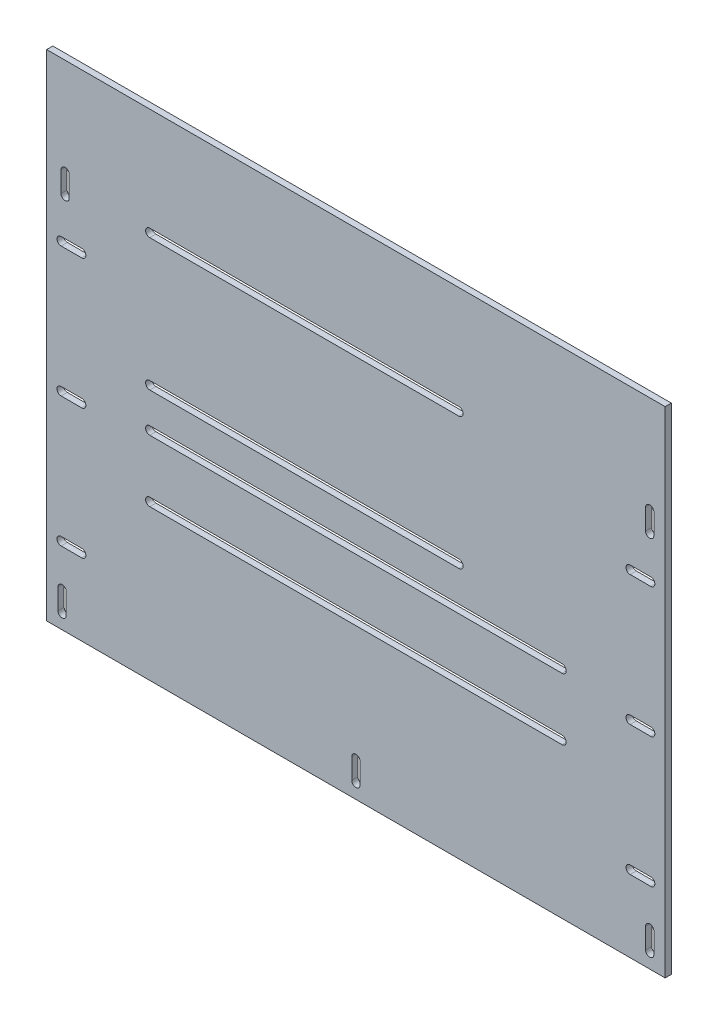
SolidWorks part; units mm, degrees
ref_plane "Front Plane" through (0, 0, 0) normal (0, 0, 1) x (1, 0, 0)
ref_plane "Top Plane" through (0, 0, 0) normal (0, 1, 0) x (1, 0, 0)
ref_plane "Right Plane" through (0, 0, 0) normal (1, 0, 0) x (0, 0, -1)
sketch "Sketch1" plane through (0, 0, 0) normal (0, 0, 1) x (1, 0, 0)
  line L1 (-150, 100) -> (150, 100)
  line L2 (-150, 100) -> (-150, -100)
  line L3 (-150, -100) -> (150, -100)
  line L4 (150, 100) -> (150, -100)
  line L5 (-150, 100) -> (150, -100) construction
  line L6 (-150, -100) -> (150, 100) construction
  point P0 (0, 0)
  dimension "D1" = 200
  dimension "D2" = 300
extrude "Boss-Extrude1" add sketch "Sketch1" along normal blind 3
sketch "Sketch2" plane through (0, 0, 0) normal (0, 0, -1) x (-1, 0, 0)
  line L0 (-100, -25) -> (100, -25) construction
  line L1 (-100, -23) -> (100, -23)
  line L2 (-100, -27) -> (100, -27)
  line L3 (150, 100) -> (150, -100) construction
  line L4 (150, -100) -> (-150, -100) construction
  line L5 (-100, 5) -> (100, 5) construction
  line L6 (-100, 7) -> (100, 7)
  line L7 (-100, 3) -> (100, 3)
  line L8 (-50, 24) -> (100, 24) construction
  line L9 (-50, 26) -> (100, 26)
  line L10 (-50, 22) -> (100, 22)
  line L11 (-50, 88) -> (100, 88) construction
  line L12 (-50, 90) -> (100, 90)
  line L13 (-50, 86) -> (100, 86)
  arc A0 (-100, -23) -> (-100, -27) centre (-100, -25) ccw
  arc A1 (100, -27) -> (100, -23) centre (100, -25) ccw
  arc A2 (-100, 7) -> (-100, 3) centre (-100, 5) ccw
  arc A3 (100, 3) -> (100, 7) centre (100, 5) ccw
  arc A4 (-50, 26) -> (-50, 22) centre (-50, 24) ccw
  arc A5 (100, 22) -> (100, 26) centre (100, 24) ccw
  arc A6 (-50, 90) -> (-50, 86) centre (-50, 88) ccw
  arc A7 (100, 86) -> (100, 90) centre (100, 88) ccw
  point P2 (0, -25)
  point P13 (0, 5)
  point P20 (25, 24)
  point P25 (25, 88)
  dimension "D1" = 2
  dimension "D5" = 2
  dimension "D7" = 2
  dimension "D8" = 2
  dimension "D2" = 200
  dimension "D3" = 50
  dimension "D4" = 75
  dimension "D6" = 30
  dimension "D9" = 124
  dimension "D10" = 64
  dimension "D11" = 50
  dimension "D12" = 150
  dimension "D13" = 150
  dimension "D14" = 50
extrude "Cut-Extrude1" cut sketch "Sketch2" against normal blind 3
sketch "Sketch3" plane through (0, 0, 0) normal (0, 0, -1) x (-1, 0, 0)
  line L13 (141.0448, 93) -> (141.0448, 83) construction
  line L14 (143.0448, 93) -> (143.0448, 83)
  line L15 (139.0448, 93) -> (139.0448, 83)
  line L16 (-150, 100) -> (150, 100) construction
  arc A8 (143.0448, 93) -> (139.0448, 93) centre (141.0448, 93) ccw
  arc A9 (139.0448, 83) -> (143.0448, 83) centre (141.0448, 83) ccw
  point P30 (141.0448, 88)
  dimension "D11" = 2
  dimension "D14" = 10
  dimension "D15" = 7
extrude "Cut-Extrude2" cut sketch "Sketch3" against normal blind 10
sketch "Sketch4" plane through (0, 0, 0) normal (0, 0, -1) x (-1, 0, 0)
  line L0 (142.5, -83) -> (142.5, -93) construction
  line L1 (144.5, -83) -> (144.5, -93)
  line L2 (140.5, -83) -> (140.5, -93)
  line L3 (150, 100) -> (150, -100) construction
  line L4 (150, -100) -> (-150, -100) construction
  arc A0 (144.5, -83) -> (140.5, -83) centre (142.5, -83) ccw
  arc A1 (140.5, -93) -> (144.5, -93) centre (142.5, -93) ccw
  point P2 (142.5, -88)
  dimension "D1" = 2
  dimension "D2" = 10
  dimension "D3" = 7.5
  dimension "D4" = 7
extrude "Cut-Extrude3" cut sketch "Sketch4" against normal blind 10
sketch "Sketch5" plane through (0, 0, 0) normal (0, 0, -1) x (-1, 0, 0)
  line L0 (-142.5, 93) -> (-142.5, 83) construction
  line L1 (-140.5, 93) -> (-140.5, 83)
  line L2 (-144.5, 93) -> (-144.5, 83)
  line L6 (-150, 100) -> (150, 100) construction
  line L7 (-150, -100) -> (-150, 100) construction
  arc A0 (-140.5, 93) -> (-144.5, 93) centre (-142.5, 93) ccw
  arc A1 (-144.5, 83) -> (-140.5, 83) centre (-142.5, 83) ccw
  point P2 (-142.5, 88)
  dimension "D1" = 2
  dimension "D2" = 10
  dimension "D3" = 7
  dimension "D4" = 7.5
extrude "Cut-Extrude4" cut sketch "Sketch5" against normal blind 10
sketch "Sketch6" plane through (0, 0, 0) normal (0, 0, -1) x (-1, 0, 0)
  line L0 (-142.5, -83) -> (-142.5, -93) construction
  line L1 (-140.5, -83) -> (-140.5, -93)
  line L2 (-144.5, -83) -> (-144.5, -93)
  line L3 (-150, -100) -> (-150, 100) construction
  line L4 (150, -100) -> (-150, -100) construction
  arc A0 (-140.5, -83) -> (-144.5, -83) centre (-142.5, -83) ccw
  arc A1 (-144.5, -93) -> (-140.5, -93) centre (-142.5, -93) ccw
  point P2 (-142.5, -88)
  dimension "D3" = 2
  dimension "D1" = 7.5
  dimension "D2" = 10
  dimension "D4" = 7
extrude "Cut-Extrude5" cut sketch "Sketch6" against normal blind 10
sketch "Sketch7" plane through (0, 0, 0) normal (0, 0, -1) x (-1, 0, 0)
  line L0 (0, -83) -> (0, -93) construction
  line L1 (2, -83) -> (2, -93)
  line L2 (-2, -83) -> (-2, -93)
  line L3 (150, -100) -> (-150, -100) construction
  line L4 (-150, -100) -> (-150, 100) construction
  arc A0 (2, -83) -> (-2, -83) centre (0, -83) ccw
  arc A1 (-2, -93) -> (2, -93) centre (0, -93) ccw
  point P2 (0, -88)
  dimension "D1" = 2
  dimension "D2" = 10
  dimension "D3" = 7
  dimension "D4" = 150
extrude "Cut-Extrude6" cut sketch "Sketch7" against normal blind 10
sketch "Sketch8" plane through (0, 0, 0) normal (0, 0, -1) x (-1, 0, 0)
  line L0 (-143, 63) -> (-133, 63) construction
  line L1 (-143, 65) -> (-133, 65)
  line L2 (-143, 61) -> (-133, 61)
  line L3 (-143, -63) -> (-133, -63) construction
  line L4 (-143, -61) -> (-133, -61)
  line L5 (-143, -65) -> (-133, -65)
  line L6 (-143, 0) -> (-133, 0) construction
  line L7 (-143, 2) -> (-133, 2)
  line L8 (-143, -2) -> (-133, -2)
  line L9 (-150, 100) -> (150, 100) construction
  line L10 (-150, -100) -> (-150, 100) construction
  line L11 (150, -100) -> (-150, -100) construction
  arc A0 (-143, 65) -> (-143, 61) centre (-143, 63) ccw
  arc A1 (-133, 61) -> (-133, 65) centre (-133, 63) ccw
  arc A2 (-143, -61) -> (-143, -65) centre (-143, -63) ccw
  arc A3 (-133, -65) -> (-133, -61) centre (-133, -63) ccw
  arc A4 (-143, 2) -> (-143, -2) centre (-143, 0) ccw
  arc A5 (-133, -2) -> (-133, 2) centre (-133, 0) ccw
  point P2 (-138, 63)
  point P9 (-138, -63)
  point P14 (-138, 0)
  dimension "D1" = 2
  dimension "D2" = 2
  dimension "D3" = 2
  dimension "D4" = 10
  dimension "D5" = 10
  dimension "D6" = 10
  dimension "D7" = 37
  dimension "D8" = 7
  dimension "D9" = 100
  dimension "D10" = 7
  dimension "D11" = 37
  dimension "D12" = 7
extrude "Cut-Extrude7" cut sketch "Sketch8" against normal blind 10
sketch "Sketch9" plane through (0, 0, 0) normal (0, 0, -1) x (-1, 0, 0)
  line L0 (133, 63) -> (143, 63) construction
  line L1 (133, 65) -> (143, 65)
  line L2 (133, 61) -> (143, 61)
  line L3 (133, 0) -> (143, 0) construction
  line L4 (133, 2) -> (143, 2)
  line L5 (133, -2) -> (143, -2)
  line L6 (133, -63) -> (143, -63) construction
  line L7 (133, -61) -> (143, -61)
  line L8 (133, -65) -> (143, -65)
  line L9 (150, 100) -> (150, -100) construction
  arc A0 (133, 65) -> (133, 61) centre (133, 63) ccw
  arc A1 (143, 61) -> (143, 65) centre (143, 63) ccw
  arc A2 (133, 2) -> (133, -2) centre (133, 0) ccw
  arc A3 (143, -2) -> (143, 2) centre (143, 0) ccw
  arc A4 (133, -61) -> (133, -65) centre (133, -63) ccw
  arc A5 (143, -65) -> (143, -61) centre (143, -63) ccw
  point P3 (138, 63)
  point P8 (138, 0)
  point P17 (138, -63)
  dimension "D1" = 2
  dimension "D4" = 2
  dimension "D7" = 2
  dimension "D2" = 10
  dimension "D3" = 7
  dimension "D5" = 10
  dimension "D6" = 7
  dimension "D8" = 10
  dimension "D9" = 7
extrude "Cut-Extrude8" cut sketch "Sketch9" against normal blind 10
sketch "Sketch10" plane through (0, 100, 0) normal (0, 1, 0) x (1, 0, 0)
  line L1 (-150, 0) -> (150, 0)
  line L2 (-150, 0) -> (-150, -3)
  line L3 (-150, -3) -> (150, -3)
  line L4 (150, 0) -> (150, -3)
extrude "Boss-Extrude2" add sketch "Sketch10" along normal blind 40
